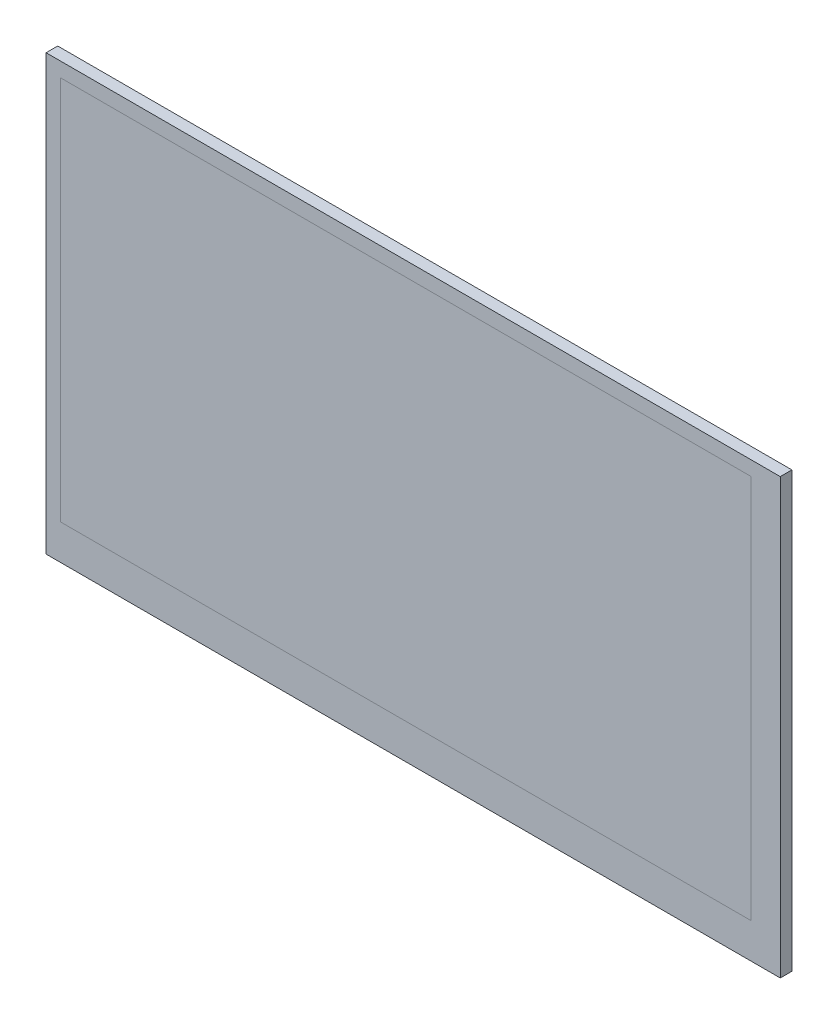
SolidWorks part; units mm, degrees
ref_plane "Front Plane" through (0, 0, 0) normal (0, 0, 1) x (1, 0, 0)
ref_plane "Top Plane" through (0, 0, 0) normal (0, 1, 0) x (1, 0, 0)
ref_plane "Right Plane" through (0, 0, 0) normal (1, 0, 0) x (0, 0, -1)
sketch "Sketch1" plane through (0, 0, 0) normal (0, 0, 1) x (1, 0, 0)
  line L1 (-82, 48.5) -> (82, 48.5)
  line L2 (-82, 48.5) -> (-82, -48.5)
  line L3 (-82, -48.5) -> (82, -48.5)
  line L4 (82, 48.5) -> (82, -48.5)
  line L5 (-82, 48.5) -> (82, -48.5) construction
  line L6 (-82, -48.5) -> (82, 48.5) construction
  point P0 (0, 0)
  dimension "D1" = 97
  dimension "D2" = 164
extrude "Boss-Extrude1" add sketch "Sketch1" along normal blind 2.6
sketch "Sketch2" plane through (0, 0, 2.6) normal (0, 0, 1) x (1, 0, 0)
  line L0 (82, 48.5) -> (-82, 48.5) construction
  line L1 (-78.8, 45.26) -> (75.41, 45.26)
  line L2 (-78.8, 45.26) -> (-78.8, -40.66)
  line L3 (-78.8, -40.66) -> (75.41, -40.66)
  line L4 (75.41, 45.26) -> (75.41, -40.66)
  line L5 (82, -48.5) -> (82, 48.5) construction
  dimension "D1" = 154.21
  dimension "D2" = 85.92
  dimension "D3" = 3.24
  dimension "D4" = 6.59
extrude "Cut-Extrude1" cut sketch "Sketch2" against normal blind 1
sketch "Sketch3" plane through (0, 0, 2.6) normal (0, 0, 1) x (1, 0, 0)
  line L1 (-78.8, 45.26) -> (75.41, 45.26)
  line L2 (-78.8, 45.26) -> (-78.8, -40.66)
  line L3 (-78.8, -40.66) -> (75.41, -40.66)
  line L4 (75.41, 45.26) -> (75.41, -40.66)
extrude "Boss-Extrude3" add sketch "Sketch3" against normal up to next separate body
